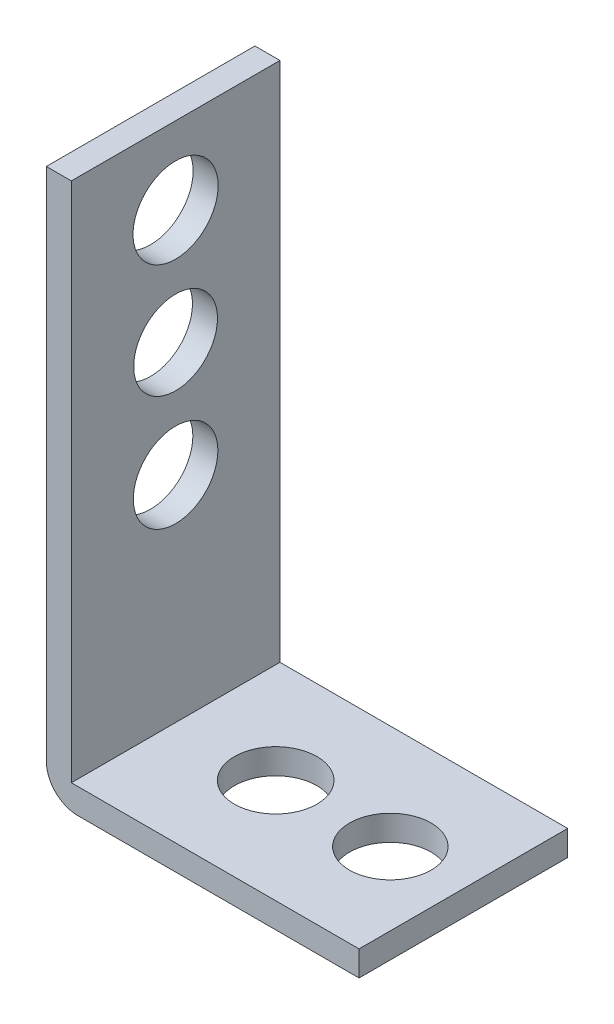
SolidWorks part; units mm, degrees
ref_plane "Front Plane" through (0, 0, 0) normal (0, 0, 1) x (1, 0, 0)
ref_plane "Top Plane" through (0, 0, 0) normal (0, 1, 0) x (1, 0, 0)
ref_plane "Right Plane" through (0, 0, 0) normal (1, 0, 0) x (0, 0, -1)
sketch "Sketch1" plane through (0, 0, 0) normal (0, 1, 0) x (1, 0, 0)
  line L1 (0, 0) -> (-38.1, 0)
  line L2 (0, 0) -> (0, 25.4152)
  line L3 (0, 25.4152) -> (-38.1, 25.4152)
  line L4 (-38.1, 0) -> (-38.1, 25.4152)
extrude "Boss-Extrude1" add sketch "Sketch1" along normal blind 3.0734
sketch "Sketch2" plane through (-38.1, 0, 0) normal (-1, 0, 0) x (0, 0, 1)
  line L1 (-25.4152, 3.0734) -> (2.7594, 3.0734)
  line L2 (-25.4152, 3.0734) -> (-25.4152, 66.5734)
  line L3 (-25.4152, 66.5734) -> (2.7594, 66.5734)
  line L4 (2.7594, 3.0734) -> (2.7594, 66.5734)
extrude "Boss-Extrude2" add sketch "Sketch2" against normal blind 3.048
sketch "Sketch3" plane through (-35.052, 0, 0) normal (1, 0, 0) x (0, 0, -1)
  line L0 (-2.7594, 66.5734) -> (25.4152, 66.5734) construction
  line L1 (-2.7594, 3.0734) -> (0, 3.0734)
  line L2 (-2.7594, 3.0734) -> (-2.7594, 66.5734)
  line L3 (-2.7594, 66.5734) -> (0, 66.5734)
  line L4 (0, 3.0734) -> (0, 66.5734)
extrude "Cut-Extrude1" cut sketch "Sketch3" against normal blind 3.048
fillet "Fillet1" radius 3.81 1 edges at (-38.1, 0, -12.7076)
sketch "Sketch4" plane through (-35.052, 0, 0) normal (1, 0, 0) x (0, 0, -1)
  circle A0 centre (12.7, 57.15) radius 5.1857
  circle A1 centre (12.7, 43.18) radius 5.1054
  circle A2 centre (12.7, 29.21) radius 5.1516
  point P6 (0, 0)
  point P7 (0, 0)
  point P8 (0, 0)
  point P9 (0, 0)
extrude "Cut-Extrude2" cut sketch "Sketch4" against normal blind 3.048
sketch "Sketch5" plane through (0, 0, 0) normal (0, -1, 0) x (-1, 0, 0)
  circle A0 centre (22.86, 12.7) radius 5.0273
  circle A1 centre (8.89, 12.7) radius 4.9744
  point P4 (0, 0)
  point P5 (0, 0)
  point P6 (0, 0)
  point P7 (0, 0)
  point P8 (0, 0)
  point P9 (0, 0)
extrude "Cut-Extrude3" cut sketch "Sketch5" against normal blind 3.556
